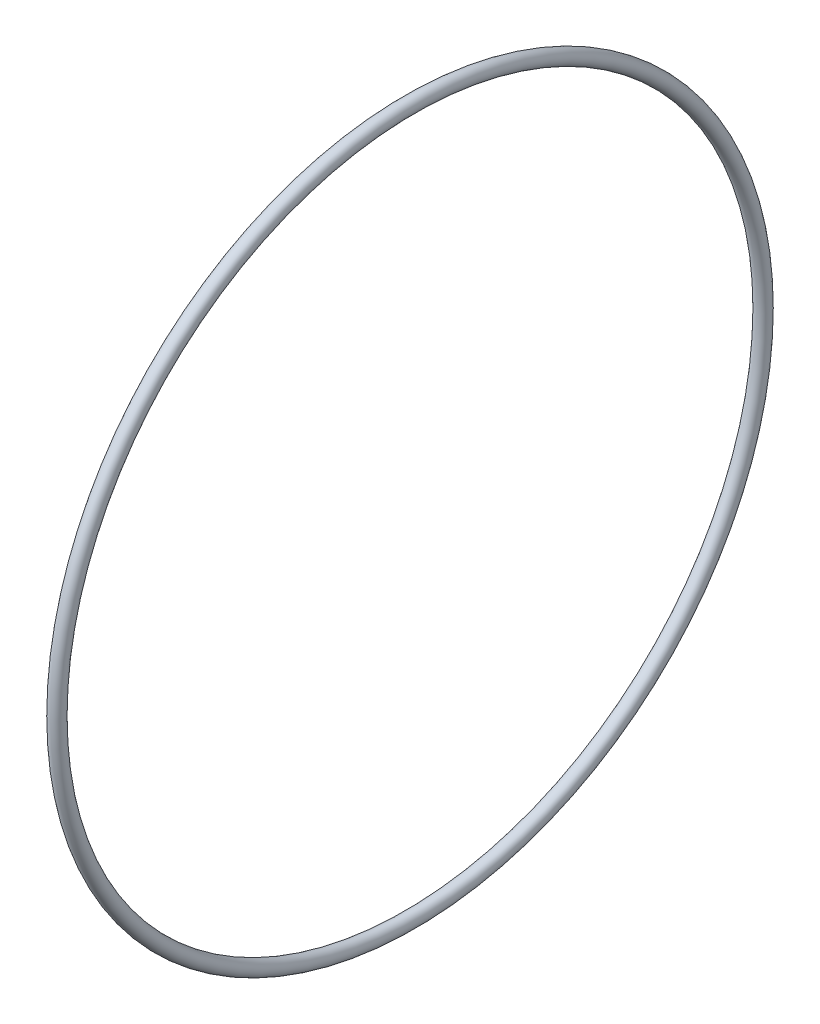
SolidWorks part; units mm, degrees
material "EPICHLOROHYDRIN"
ref_plane "Front Plane" through (0, 0, 0) normal (0, 0, 1) x (1, 0, 0)
ref_plane "Top Plane" through (0, 0, 0) normal (0, 1, 0) x (1, 0, 0)
ref_plane "Right Plane" through (0, 0, 0) normal (1, 0, 0) x (0, 0, -1)
sketch "Sketch1" plane through (0, 0, 0) normal (0, 0, 1) x (1, 0, 0)
  line L0 (-22.1809, 0) -> (22.1809, 0) construction
  line L1 (0, -14.8159) -> (0, 14.8159) construction
  circle A0 centre (0, 62.23) radius 1.27
  point P4 (0, 0)
  point P8 (0, 0)
  dimension "D1" = 2.54
  dimension "D2" = 62.23
revolve "Revolve2" add sketch "Sketch1" angle 360 about L0
